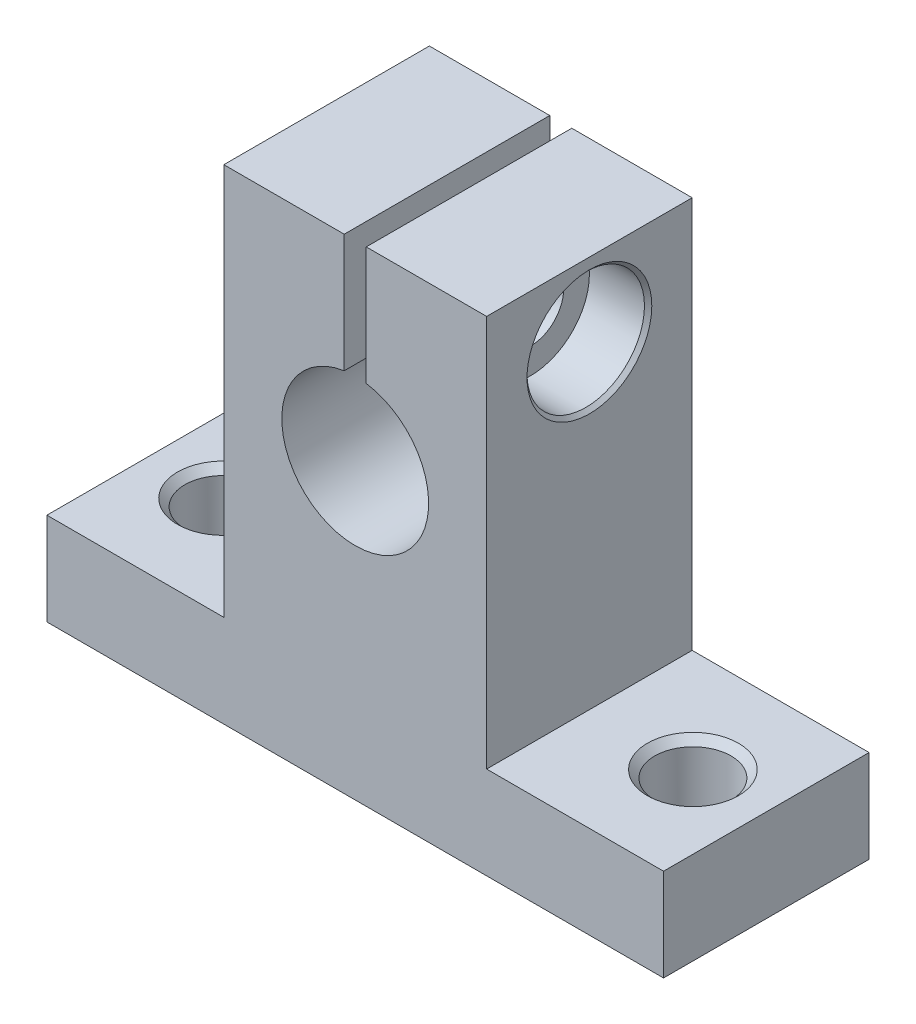
SolidWorks part; units mm, degrees
ref_plane "Front Plane" through (0, 0, 0) normal (0, 0, 1) x (1, 0, 0)
ref_plane "Top Plane" through (0, 0, 0) normal (0, 1, 0) x (1, 0, 0)
ref_plane "Right Plane" through (0, 0, 0) normal (1, 0, 0) x (0, 0, -1)
sketch "Sketch1" plane through (0, 0, 0) normal (0, 0, 1) x (1, 0, 0)
  line L0 (0, 0) -> (0, 33) construction
  line L1 (-21, 6.3) -> (-8.95, 6.3)
  line L2 (-21, 6.3) -> (-21, 0)
  line L3 (-21, 0) -> (21, 0)
  line L4 (21, 6.3) -> (21, 0)
  line L9 (-8.95, 33) -> (-0.75, 33)
  line L10 (-8.95, 33) -> (-8.95, 6.3)
  line L12 (8.95, 33) -> (8.95, 6.3)
  line L13 (-0.75, 33) -> (-0.75, 24.9434)
  line L14 (0.75, 33) -> (0.75, 24.9434)
  line L15 (0.75, 33) -> (8.95, 33)
  line L16 (8.95, 6.3) -> (21, 6.3)
  arc A0 (-0.75, 24.9434) -> (0.75, 24.9434) centre (0, 20) ccw
  dimension "D5" = 10
  dimension "D6" = 20
  dimension "D1" = 42
  dimension "D2" = 6.3
  dimension "D3" = 26.7
  dimension "D4" = 17.9
  dimension "D7" = 1.5
extrude "Boss-Extrude1" add sketch "Sketch1" along normal mid plane 14
sketch "Sketch2" plane through (0, 6.3, 0) normal (0, 1, 0) x (1, 0, 0)
  line L0 (-16, 0) -> (16, 0) construction
  circle A0 centre (16, 0) radius 2.6
  circle A1 centre (-16, 0) radius 2.6
  point P4 (0, 0)
  dimension "D1" = 5.2
  dimension "D3" = 32
extrude "Cut-Extrude1" cut sketch "Sketch2" against normal up to next
chamfer "Chamfer1" distance 0.5 angle 45 2 edges at (-16, 6.3, 2.6) (16, 6.3, 2.6)
hole_wizard "CBORE for M4 SHCS2" positions "Sketch3" profile "Sketch4" counterbore size "M4" standard "ANSI Metric" end condition up to next
sketch "Sketch3" plane through (8.95, 0, 0) normal (1, 0, 0) x (0, 0, -1)
  line L0 (0, 33) -> (0, 28) construction
  line L1 (-7, 33) -> (7, 33) construction
  point P2 (0, 28)
  dimension "D1" = 5
sketch "Sketch4" plane through (8.95, 28, 0) normal (0, 1, 0) x (0, 0, -1)
  line L0 (0, 0) -> (0, 8.2)
  line L1 (0, 8.2) -> (2.25, 8.2)
  line L3 (2.25, 8.2) -> (2.25, 4)
  line L4 (4, 4) -> (2.25, 4)
  line L5 (4, 4) -> (4, 0.25)
  line L6 (4, 0.25) -> (4.25, 0)
  line L7 (4.25, 0) -> (0, 0)
  line L8 (-4, 0.25) -> (-4.25, 0) construction
  line L11 (0, -6.35) -> (0, 107.95) construction
  dimension "Thru Hole Dia." = 4.5
  dimension "Thru Hole Depth" = 8.2
  dimension "C'Bore Dia." = 8
  dimension "C'Bore Depth" = 4
  dimension "Near C'Sink Dia." = 8.5
  dimension "Near C'Sink Angle" = 90
hole_wizard "M4x0.7 Tapped Hole1" positions "Sketch5" profile "Sketch6" tap size "M4x0.7" standard "ANSI Metric" end condition up to next
sketch "Sketch5" plane through (-0.75, 0, 0) normal (1, 0, 0) x (0, 0, -1)
  point P0 (0, 28)
sketch "Sketch6" plane through (-0.75, 28, 0) normal (0, 1, 0) x (0, 0, -1)
  line L0 (0, 0) -> (0, 8.2)
  line L1 (0, 8.2) -> (1.65, 8.2)
  line L2 (1.65, 8.2) -> (1.65, 0)
  line L5 (1.65, 0) -> (0, 0)
  line L11 (0, -6.35) -> (0, 107.95) construction
  dimension "Thru Tap Drill Dia." = 3.3
  dimension "Thru Tap Drill Depth" = 8.2
cosmetic thread "Hole Thread1" parameters "D2"=4
